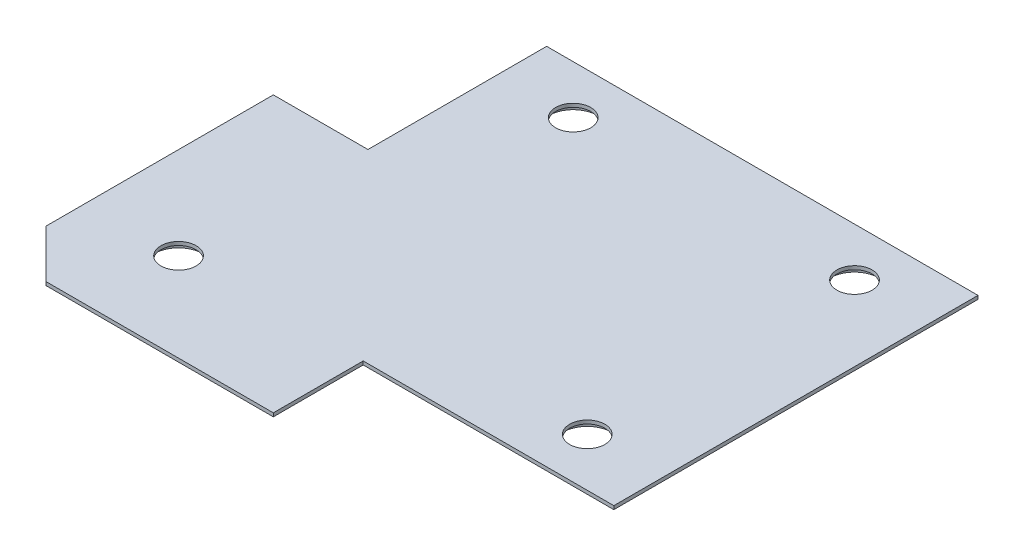
SolidWorks part; units mm, degrees
ref_plane "Front Plane" through (0, 0, 0) normal (0, 0, 1) x (1, 0, 0)
ref_plane "Top Plane" through (0, 0, 0) normal (0, 1, 0) x (1, 0, 0)
ref_plane "Right Plane" through (0, 0, 0) normal (1, 0, 0) x (0, 0, -1)
sketch "Sketch1" plane through (0, 0, 0) normal (0, 1, 0) x (1, 0, 0)
  line L1 (-1.7825, -28.3447) -> (33.8509, -28.3447)
  line L2 (-31.4806, 2.0264) -> (-31.4806, 27.4359)
  line L3 (-31.4806, 27.4359) -> (33.8509, 27.4359)
  line L4 (33.8509, -28.3447) -> (33.8509, 27.4359)
  line L7 (-44.9335, -41.1246) -> (-1.7825, -41.1246)
  line L8 (-44.9335, -41.1246) -> (-44.9335, 2.0264)
  line L9 (-44.9335, 2.0264) -> (-31.4806, 2.0264)
  line L10 (-1.7825, -41.1246) -> (-1.7825, -28.3447)
  point P0 (0, 0)
extrude "Boss-Extrude1" add sketch "Sketch1" along normal blind 2
sketch "Sketch2" plane through (0, 2, 0) normal (0, 1, 0) x (1, 0, 0)
  line L0 (-20.026, -21.3446) -> (-55.2841, -20.4558)
  line L1 (-55.2841, -20.4558) -> (-55.2841, -41.0477)
  line L2 (-55.2841, -41.0477) -> (-20.026, -21.3446)
chamfer "Chamfer1" distance 8 angle 45 1 edges at (-44.9335, 1, 41.1246)
sketch "Sketch3" plane through (0, 2, 0) normal (0, 1, 0) x (1, 0, 0)
  line L0 (-29.4806, 25.4359) -> (31.8509, 25.4359)
  line L1 (31.8509, 25.4359) -> (31.8509, -26.3447)
  line L2 (31.8509, -26.3447) -> (-3.7825, -26.3447)
  line L3 (-3.7825, -26.3447) -> (-3.7825, -39.1246)
  line L4 (-3.7825, -39.1246) -> (-36.1051, -39.1246)
  line L5 (-36.1051, -39.1246) -> (-42.9335, -32.2962)
  line L6 (-42.9335, -32.2962) -> (-42.9335, 0.0264)
  line L7 (-42.9335, 0.0264) -> (-29.4806, 0.0264)
  line L8 (-29.4806, 0.0264) -> (-29.4806, 25.4359)
  line L9 (-31.4806, 2.0264) -> (-44.9335, 2.0264) construction
  line L10 (-44.9335, 2.0264) -> (-44.9335, -33.1246) construction
  line L11 (-44.9335, -33.1246) -> (-36.9335, -41.1246) construction
  line L12 (-36.9335, -41.1246) -> (-1.7825, -41.1246) construction
  line L13 (-1.7825, -41.1246) -> (-1.7825, -28.3447) construction
  line L14 (-1.7825, -28.3447) -> (33.8509, -28.3447) construction
  line L15 (33.8509, -28.3447) -> (33.8509, 27.4359) construction
  line L16 (-31.4806, 27.4359) -> (-31.4806, 2.0264) construction
  line L17 (33.8509, 27.4359) -> (-31.4806, 27.4359) construction
  dimension "D1" = 2
  dimension "D2" = 2
  dimension "D3" = 2
  dimension "D4" = 2
  dimension "D5" = 2
  dimension "D6" = 2
  dimension "D7" = 2
  dimension "D8" = 2
  dimension "D9" = 2
extrude "Boss-Extrude2" add sketch "Sketch3" along normal blind 1.5
sketch "Sketch4" plane through (0, 0, 0) normal (0, -1, 0) x (1, 0, 0)
  line L1 (49.8844, -45.7944) -> (-49.8844, -45.7944)
  line L2 (49.8844, -45.7944) -> (49.8844, 45.7944)
  line L3 (49.8844, 45.7944) -> (-49.8844, 45.7944)
  line L4 (-49.8844, -45.7944) -> (-49.8844, 45.7944)
  line L5 (49.8844, -45.7944) -> (-49.8844, 45.7944) construction
  line L6 (49.8844, 45.7944) -> (-49.8844, -45.7944) construction
  point P0 (0, 0)
extrude "Cut-Extrude1" cut sketch "Sketch4" against normal blind 2
sketch "Sketch5" plane through (0, 3.5, 0) normal (0, 1, 0) x (1, 0, 0)
  line L0 (1.1852, 18.5456) -> (1.1852, -0.4544) construction
  line L5 (-3.7825, -26.3447) -> (31.8509, -26.3447) construction
  line L6 (31.8509, -0.4544) -> (-18.8148, -0.4544) construction
  line L7 (31.8509, -26.3447) -> (31.8509, 25.4359) construction
  line L8 (31.8509, 25.4359) -> (-29.4806, 25.4359) construction
  line L9 (-42.9335, 0.0264) -> (-42.9335, -32.2962) construction
  line L10 (21.1852, -0.4544) -> (21.1852, 18.5456) construction
  line L11 (21.1852, -19.4544) -> (1.1852, -19.4544) construction
  line L12 (21.1852, -19.4544) -> (21.1852, -0.4544) construction
  line L13 (1.1852, 18.5456) -> (-18.8148, 18.5456) construction
  line L14 (-18.8148, -19.4544) -> (-18.8148, -0.4544) construction
  line L15 (21.1852, -19.4544) -> (1.1852, -0.4544) construction
  line L16 (1.1852, -0.4544) -> (-18.8148, -19.4544) construction
  line L17 (21.1852, 18.5456) -> (1.1852, -0.4544) construction
  line L18 (21.1852, 18.5456) -> (1.1852, 18.5456) construction
  line L19 (1.1852, 25.4359) -> (1.1852, 18.5456) construction
  line L20 (1.1852, -0.4544) -> (-18.8148, 18.5456) construction
  line L21 (-18.8148, -0.4544) -> (-18.8148, 18.5456) construction
  line L22 (-18.8148, -0.4544) -> (-42.9335, -0.4544) construction
  line L23 (1.1852, -19.4544) -> (-18.8148, -19.4544) construction
  line L24 (1.1852, -0.4544) -> (1.1852, -19.4544) construction
  line L25 (1.1852, -19.4544) -> (1.1852, -26.3447) construction
  line L26 (-39.5193, -35.7104) -> (-18.8148, -16.0411) construction
  line L27 (-23.2619, -30.4944) -> (-25.7619, -30.4944) construction
  line L28 (-42.9335, -32.2962) -> (-36.1051, -39.1246) construction
  line L29 (-29.8548, -26.5291) -> (-29.8548, -16.0411) construction
  line L30 (-29.8548, -16.0411) -> (-18.8148, -16.0411) construction
  circle A0 centre (-18.8148, 18.5456) radius 2.5
  circle A1 centre (21.1852, 18.5456) radius 2.5
  circle A2 centre (21.1852, -19.4544) radius 2.5
  circle A4 centre (-29.8548, -26.5291) radius 2.5
  point P0 (0, 0)
  point P14 (1.1852, -0.4544)
  dimension "D3" = 5
  dimension "D4" = 11.04
  dimension "D1" = 40
  dimension "D2" = 38
extrude "Cut-Extrude2" cut sketch "Sketch5" against normal blind 2
sketch "Sketch6" plane through (0, 2, 0) normal (0, -1, 0) x (1, 0, 0)
  circle A0 centre (-29.8548, 26.5291) radius 3.5
  circle A1 centre (21.1852, 19.4544) radius 3.5
  circle A2 centre (-18.8148, -18.5456) radius 3.5
  circle A3 centre (21.1852, -18.5456) radius 3.5
  dimension "D1" = 7
extrude "Cut-Extrude3" cut sketch "Sketch6" against normal blind 1
sketch "Sketch7" plane through (0, 2, 0) normal (0, -1, 0) x (1, 0, 0)
  circle A0 centre (-29.8548, 26.5291) radius 4
  circle A1 centre (-29.8548, 26.5291) radius 5
  circle A2 centre (21.1852, 19.4544) radius 4
  circle A3 centre (21.1852, 19.4544) radius 5
  circle A4 centre (21.1852, -18.5456) radius 4
  circle A5 centre (21.1852, -18.5456) radius 5
  circle A6 centre (-18.8148, -18.5456) radius 4
  circle A7 centre (-18.8148, -18.5456) radius 5
  dimension "D1" = 1
chamfer "Chamfer2" distance 1 angle 45 9 edges at (-19.9438, 2, 39.1246) (-3.7825, 2, 32.7346) (14.0342, 2, 26.3447) (31.8509, 2, 0.4544) (1.1852, 2, -25.4359) (-29.4806, 2, -12.7312) (-36.2071, 2, -0.0264) (-39.5193, 2, 35.7104) (-42.9335, 2, 16.1349)
